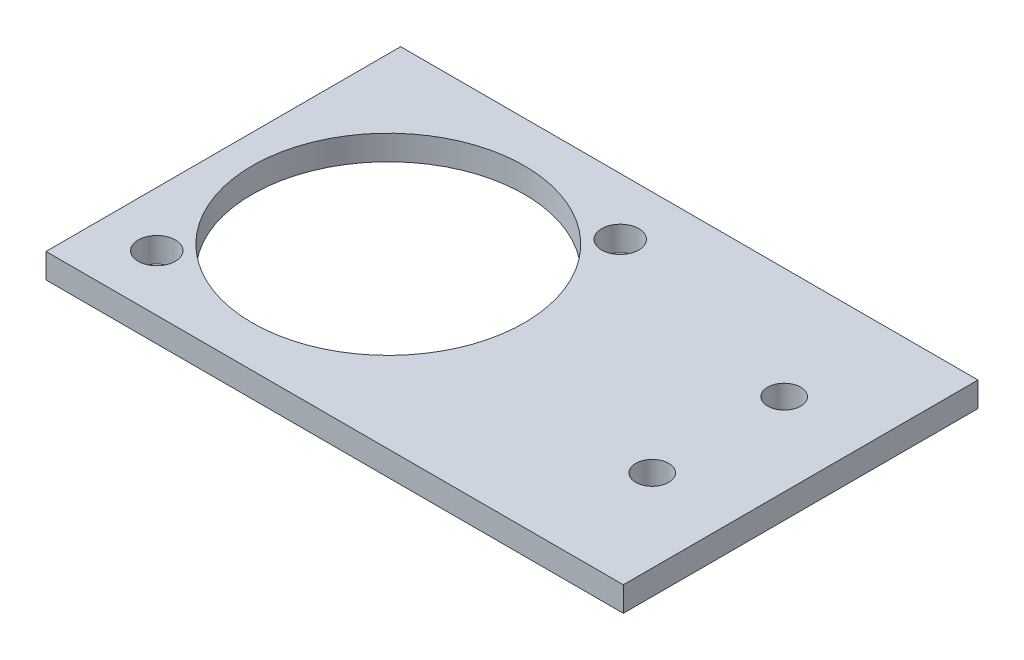
SolidWorks part; units mm, degrees
ref_plane "Front Plane" through (0, 0, 0) normal (0, 0, 1) x (1, 0, 0)
ref_plane "Top Plane" through (0, 0, 0) normal (0, 1, 0) x (1, 0, 0)
ref_plane "Right Plane" through (0, 0, 0) normal (1, 0, 0) x (0, 0, -1)
sketch "Sketch1" plane through (0, 0, 0) normal (0, 1, 0) x (1, 0, 0)
  line L0 (-35, 0) -> (35, 0) construction
  line L1 (-35, 21.5) -> (35, 21.5)
  line L2 (-35, 21.5) -> (-35, -21.5)
  line L3 (-35, -21.5) -> (35, -21.5)
  line L4 (35, 21.5) -> (35, -21.5)
  line L5 (-35, 21.5) -> (35, -21.5) construction
  line L6 (-35, -21.5) -> (35, 21.5) construction
  line L7 (25, 21.5) -> (25, -21.5) construction
  circle A0 centre (-15, 0) radius 16.5
  circle A1 centre (-1.46, 14.58) radius 2.25
  circle A2 centre (-28.37, -14.7) radius 2.25
  circle A3 centre (25, 8) radius 2
  circle A4 centre (25, -8) radius 2
  point P0 (0, 0)
  dimension "D2" = 33
  dimension "D3" = 4.5
  dimension "D8" = 20
  dimension "D10" = 4
  dimension "D11" = 4
  dimension "D1" = 43
  dimension "D4" = 13.54
  dimension "D5" = 14.58
  dimension "D6" = 14.7
  dimension "D7" = 13.37
  dimension "D9" = 70
  dimension "D12" = 8
  dimension "D13" = 8
  dimension "D14" = 20
extrude "Boss-Extrude1" add sketch "Sketch1" along normal blind 3
